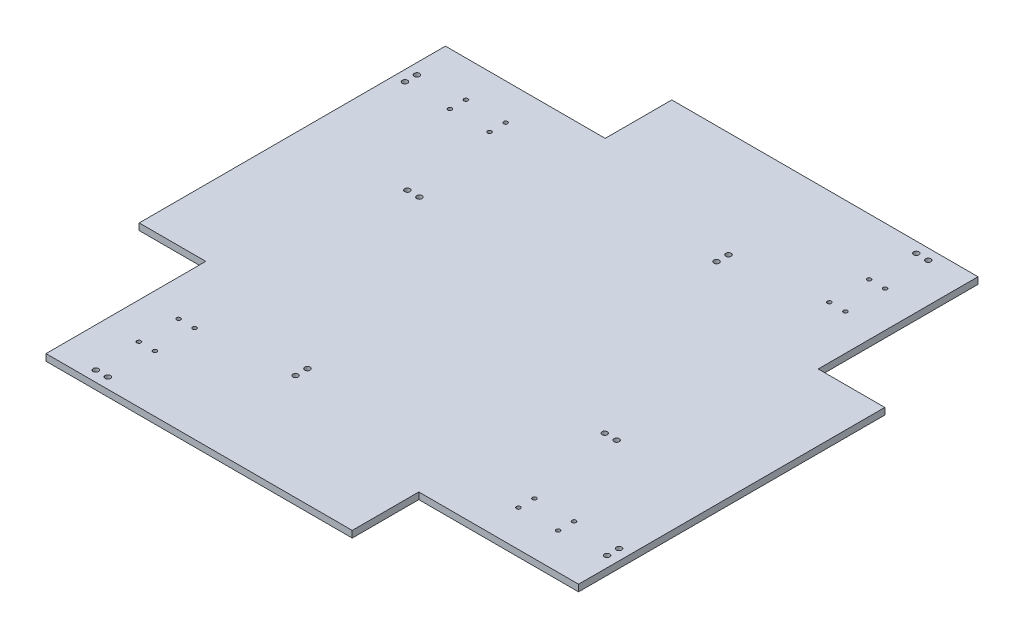
SolidWorks part; units mm, degrees
ref_plane "Front Plane" through (0, 0, 0) normal (0, 0, 1) x (1, 0, 0)
ref_plane "Top Plane" through (0, 0, 0) normal (0, 1, 0) x (1, 0, 0)
ref_plane "Right Plane" through (0, 0, 0) normal (1, 0, 0) x (0, 0, -1)
sketch "Sketch1" plane through (0, 0, 0) normal (0, 1, 0) x (1, 0, 0)
  line L1 (-36.5079, 29.0476) -> (363.4921, 29.0476)
  line L2 (-36.5079, 29.0476) -> (-36.5079, -370.9524)
  line L3 (-36.5079, -370.9524) -> (363.4921, -370.9524)
  line L4 (363.4921, 29.0476) -> (363.4921, -370.9524)
  dimension "D1" = 400
  dimension "D2" = 400
extrude "Boss-Extrude1" add sketch "Sketch1" along normal blind 5
sketch "Sketch2" plane through (0, 5, 0) normal (0, 1, 0) x (1, 0, 0)
  line L1 (-36.5079, 29.0476) -> (83.4921, 29.0476)
  line L2 (-36.5079, 29.0476) -> (-36.5079, -20.9524)
  line L3 (-36.5079, -20.9524) -> (83.4921, -20.9524)
  line L4 (83.4921, 29.0476) -> (83.4921, -20.9524)
  line L5 (363.4921, 29.0476) -> (313.4921, 29.0476)
  line L6 (363.4921, 29.0476) -> (363.4921, -90.9524)
  line L7 (363.4921, -90.9524) -> (313.4921, -90.9524)
  line L8 (313.4921, 29.0476) -> (313.4921, -90.9524)
  line L9 (363.4921, -370.9524) -> (243.4921, -370.9524)
  line L10 (363.4921, -370.9524) -> (363.4921, -320.9524)
  line L11 (363.4921, -320.9524) -> (243.4921, -320.9524)
  line L12 (243.4921, -370.9524) -> (243.4921, -320.9524)
  line L13 (-36.5079, -370.9524) -> (13.4921, -370.9524)
  line L14 (-36.5079, -370.9524) -> (-36.5079, -250.9524)
  line L15 (-36.5079, -250.9524) -> (13.4921, -250.9524)
  line L16 (13.4921, -370.9524) -> (13.4921, -250.9524)
  dimension "D1" = 120
  dimension "D2" = 50
  dimension "D3" = 120
  dimension "D4" = 50
  dimension "D5" = 120
  dimension "D6" = 50
  dimension "D7" = 50
  dimension "D8" = 120
extrude "Cut-Extrude1" cut sketch "Sketch2" against normal blind 5
sketch "Sketch3" plane through (0, 5, 0) normal (0, 1, 0) x (1, 0, 0)
  line L0 (34.4921, -20.9524) -> (34.4921, -461.6407)
  line L2 (13.4921, -299.9524) -> (475.7545, -299.9524)
  line L4 (292.4921, -320.9524) -> (292.4921, 120.4352)
  line L6 (313.4921, -41.9524) -> (-151.146, -41.9524)
  line L8 (-36.5079, -20.9524) -> (83.4921, -20.9524) construction
  line L9 (13.4921, -370.9524) -> (13.4921, -250.9524) construction
  line L10 (363.4921, -320.9524) -> (243.4921, -320.9524) construction
  line L11 (313.4921, 29.0476) -> (313.4921, -90.9524) construction
  dimension "D1" = 21
  dimension "D2" = 21
  dimension "D3" = 21
  dimension "D4" = 21
sketch "Sketch4" plane through (0, 5, 0) normal (0, 1, 0) x (1, 0, 0)
  circle A0 centre (284.0921, -212.9524) radius 2
  circle A1 centre (275.0921, -212.9524) radius 2
  circle A2 centre (284.0921, 21.0476) radius 2
  circle A3 centre (275.0921, 21.0476) radius 2
  circle A4 centre (286.2921, -13.5524) radius 1.5
  circle A5 centre (274.2921, -13.5524) radius 1.5
  circle A6 centre (286.2921, -43.3524) radius 1.5
  circle A7 centre (274.2921, -43.3524) radius 1.5
  circle A8 centre (355.4921, -291.5524) radius 2
  circle A9 centre (355.4921, -282.5524) radius 2
  circle A10 centre (320.8921, -293.7524) radius 1.5
  circle A11 centre (320.8921, -281.7524) radius 1.5
  circle A12 centre (291.0921, -293.7524) radius 1.5
  circle A13 centre (291.0921, -281.7524) radius 1.5
  circle A14 centre (121.4921, -291.5524) radius 2
  circle A15 centre (121.4921, -282.5524) radius 2
  circle A16 centre (51.8921, -362.9524) radius 2
  circle A17 centre (42.8921, -362.9524) radius 2
  circle A18 centre (52.6921, -328.3524) radius 1.5
  circle A19 centre (40.6921, -328.3524) radius 1.5
  circle A20 centre (52.6921, -298.5524) radius 1.5
  circle A21 centre (40.6921, -298.5524) radius 1.5
  circle A22 centre (51.8921, -128.9524) radius 2
  circle A23 centre (42.8921, -128.9524) radius 2
  circle A24 centre (-28.5079, -59.3524) radius 2
  circle A25 centre (-28.5079, -50.3524) radius 2
  circle A26 centre (35.8921, -60.1524) radius 1.5
  circle A27 centre (35.8921, -48.1524) radius 1.5
  circle A28 centre (6.0921, -60.1524) radius 1.5
  circle A29 centre (6.0921, -48.1524) radius 1.5
  circle A30 centre (205.4921, -59.3524) radius 2
  circle A31 centre (205.4921, -50.3524) radius 2
extrude "Cut-Extrude2" cut sketch "Sketch4" against normal up to surface (5 mm away) up to face at (163.4921, 0, 170.9524)
